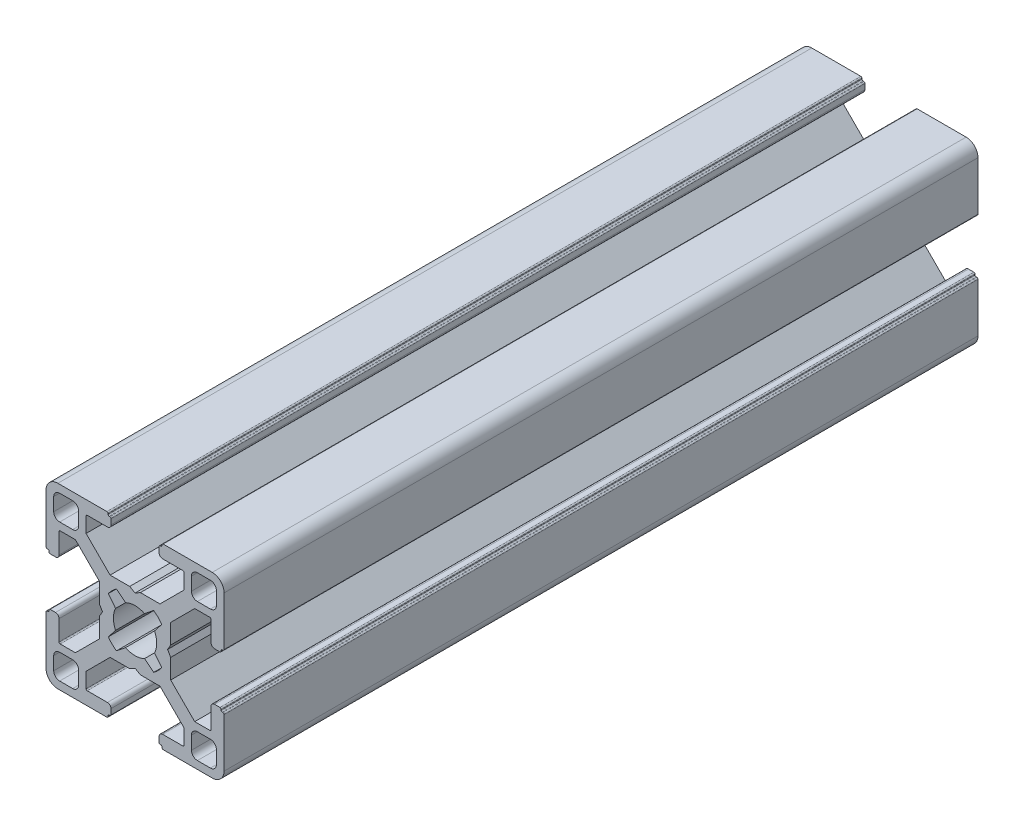
SolidWorks part; units mm, degrees
material "6061 Alloy"
ref_plane "Front" through (0, 0, 0) normal (0, 0, 1) x (1, 0, 0)
ref_plane "Top" through (0, 0, 0) normal (0, 1, 0) x (1, 0, 0)
ref_plane "Right" through (0, 0, 0) normal (1, 0, 0) x (0, 0, -1)
sketch "Sketch1" plane through (0, 0, 0) normal (0, 0, 1) x (1, 0, 0)
  line L0 (13.7, 12.7) -> (13.7, 10.5)
  line L1 (10.5, 9.5) -> (12.7, 9.5)
  line L2 (9.5, 12.7) -> (9.5, 10.5)
  line L3 (10.5, 13.7) -> (12.7, 13.7)
  line L4 (3.1359, 4.5184) -> (1.6001, 3.2806)
  line L5 (3.2806, 1.6001) -> (4.5053, 3.1547)
  line L6 (6.0045, 0.9) -> (5.4849, 0)
  line L7 (6.0045, 4.2045) -> (6.0045, 0.9)
  line L8 (0, -5.4849) -> (0.9, -6)
  line L9 (0.9, -6) -> (4.2045, -6)
  line L10 (4.2045, -6) -> (8.25, -10.05)
  line L11 (8.25, -10.05) -> (8.25, -12.6)
  line L12 (4.65, -12.8) -> (8.05, -12.8)
  line L13 (4.05, -14.3) -> (4.05, -13.4)
  line L14 (4.25, -14.5) -> (4.35, -14.5)
  line L15 (4.55, -14.8) -> (4.55, -14.7)
  line L16 (4.75, -15) -> (13, -15)
  line L17 (15, -13) -> (15, -4.75)
  line L18 (14.7, -4.55) -> (14.8, -4.55)
  line L19 (14.5, -4.35) -> (14.5, -4.25)
  line L20 (13.4, -4.05) -> (14.3, -4.05)
  line L21 (12.8, -8.05) -> (12.8, -4.65)
  line L22 (12.6, -8.25) -> (10.05, -8.25)
  line L23 (10.05, -8.25) -> (6.0045, -4.2045)
  line L24 (6.0045, -4.2045) -> (6.0045, -0.9)
  line L25 (6.0045, -0.9) -> (5.4849, 0)
  line L26 (10.05, 8.25) -> (6.0045, 4.2045)
  line L27 (12.6, 8.25) -> (10.05, 8.25)
  line L28 (12.8, 8.05) -> (12.8, 4.65)
  line L29 (13.4, 4.05) -> (14.3, 4.05)
  line L30 (14.5, 4.35) -> (14.5, 4.25)
  line L31 (14.7, 4.55) -> (14.8, 4.55)
  line L32 (15, 13) -> (15, 4.75)
  line L33 (4.75, 15) -> (13, 15)
  line L34 (4.55, 14.8) -> (4.55, 14.7)
  line L35 (4.25, 14.5) -> (4.35, 14.5)
  line L36 (4.05, 14.3) -> (4.05, 13.4)
  line L37 (4.65, 12.8) -> (8.05, 12.8)
  line L38 (8.25, 10.05) -> (8.25, 12.6)
  line L39 (4.2045, 6) -> (8.25, 10.05)
  line L40 (0.9, 6) -> (4.2045, 6)
  line L41 (0, 5.4849) -> (0.9, 6)
  line L42 (-13.7, -12.7) -> (-13.7, -10.5)
  line L43 (-10.5, -9.5) -> (-12.7, -9.5)
  line L44 (-9.5, -12.7) -> (-9.5, -10.5)
  line L45 (-10.5, -13.7) -> (-12.7, -13.7)
  line L46 (-3.1359, -4.5184) -> (-1.6001, -3.2806)
  line L47 (-3.2806, -1.6001) -> (-4.5053, -3.1547)
  line L48 (0, 5.4849) -> (-0.9, 6)
  line L49 (-0.9, 6) -> (-4.2045, 6)
  line L50 (-4.2045, 6) -> (-8.25, 10.05)
  line L51 (-8.25, 10.05) -> (-8.25, 12.6)
  line L52 (-4.65, 12.8) -> (-8.05, 12.8)
  line L53 (-4.05, 14.3) -> (-4.05, 13.4)
  line L54 (-4.25, 14.5) -> (-4.35, 14.5)
  line L55 (-4.55, 14.8) -> (-4.55, 14.7)
  line L56 (-4.75, 15) -> (-13, 15)
  line L57 (-15, 13) -> (-15, 4.75)
  line L58 (-14.7, 4.55) -> (-14.8, 4.55)
  line L59 (-14.5, 4.35) -> (-14.5, 4.25)
  line L60 (-13.4, 4.05) -> (-14.3, 4.05)
  line L61 (-12.8, 8.05) -> (-12.8, 4.65)
  line L62 (-12.6, 8.25) -> (-10.05, 8.25)
  line L63 (-10.05, 8.25) -> (-6.0045, 4.2045)
  line L64 (-6.0045, -0.9) -> (-5.4849, 0)
  line L65 (-6.0045, -4.2045) -> (-6.0045, -0.9)
  line L66 (-10.05, -8.25) -> (-6.0045, -4.2045)
  line L67 (-12.6, -8.25) -> (-10.05, -8.25)
  line L68 (-12.8, -8.05) -> (-12.8, -4.65)
  line L69 (-13.4, -4.05) -> (-14.3, -4.05)
  line L70 (-14.5, -4.35) -> (-14.5, -4.25)
  line L71 (-14.7, -4.55) -> (-14.8, -4.55)
  line L72 (-15, -13) -> (-15, -4.75)
  line L73 (-4.75, -15) -> (-13, -15)
  line L74 (-4.55, -14.8) -> (-4.55, -14.7)
  line L75 (-4.25, -14.5) -> (-4.35, -14.5)
  line L76 (-4.05, -14.3) -> (-4.05, -13.4)
  line L77 (3.2806, -1.6001) -> (4.5053, -3.1547)
  line L78 (3.1359, -4.5184) -> (1.6001, -3.2806)
  line L79 (-4.65, -12.8) -> (-8.05, -12.8)
  line L80 (-8.25, -10.05) -> (-8.25, -12.6)
  line L81 (-4.2045, -6) -> (-8.25, -10.05)
  line L82 (-0.9, -6) -> (-4.2045, -6)
  line L83 (0, -5.4849) -> (-0.9, -6)
  line L84 (10.5, -13.7) -> (12.7, -13.7)
  line L85 (9.5, -12.7) -> (9.5, -10.5)
  line L86 (10.5, -9.5) -> (12.7, -9.5)
  line L87 (13.7, -12.7) -> (13.7, -10.5)
  line L88 (-6.0045, 4.2045) -> (-6.0045, 0.9)
  line L89 (-6.0045, 0.9) -> (-5.4849, 0)
  line L90 (-3.2806, 1.6001) -> (-4.5053, 3.1547)
  line L91 (-3.1359, 4.5184) -> (-1.6001, 3.2806)
  line L92 (-10.5, 13.7) -> (-12.7, 13.7)
  line L93 (-9.5, 12.7) -> (-9.5, 10.5)
  line L94 (-10.5, 9.5) -> (-12.7, 9.5)
  line L95 (-13.7, 12.7) -> (-13.7, 10.5)
  line L96 (-23.4857, 0) -> (20.9308, 0) construction
  line L97 (0, 17.9563) -> (0, -17.361) construction
  arc A0 (13.7, 12.7) -> (12.7, 13.7) centre (12.7, 12.7) ccw
  arc A1 (12.7, 9.5) -> (13.7, 10.5) centre (12.7, 10.5) ccw
  arc A2 (9.5, 10.5) -> (10.5, 9.5) centre (10.5, 10.5) ccw
  arc A3 (10.5, 13.7) -> (9.5, 12.7) centre (10.5, 12.7) ccw
  arc A4 (1.6001, 3.2806) -> (-1.6001, 3.2806) centre (0, 0) ccw
  arc A5 (8.25, -12.6) -> (8.05, -12.8) centre (8.05, -12.6) cw
  arc A6 (4.65, -12.8) -> (4.05, -13.4) centre (4.65, -13.4) ccw
  arc A7 (4.05, -14.3) -> (4.25, -14.5) centre (4.25, -14.3) ccw
  arc A8 (4.35, -14.5) -> (4.55, -14.7) centre (4.35, -14.7) cw
  arc A9 (4.55, -14.8) -> (4.75, -15) centre (4.75, -14.8) ccw
  arc A10 (13, -15) -> (15, -13) centre (13, -13) ccw
  arc A11 (15, -4.75) -> (14.8, -4.55) centre (14.8, -4.75) ccw
  arc A12 (14.7, -4.55) -> (14.5, -4.35) centre (14.7, -4.35) cw
  arc A13 (14.5, -4.25) -> (14.3, -4.05) centre (14.3, -4.25) ccw
  arc A14 (13.4, -4.05) -> (12.8, -4.65) centre (13.4, -4.65) ccw
  arc A15 (12.8, -8.05) -> (12.6, -8.25) centre (12.6, -8.05) cw
  arc A16 (4.5053, 3.1547) -> (3.1359, 4.5184) centre (0, 0) ccw
  arc A17 (12.8, 8.05) -> (12.6, 8.25) centre (12.6, 8.05) ccw
  arc A18 (13.4, 4.05) -> (12.8, 4.65) centre (13.4, 4.65) cw
  arc A19 (14.5, 4.25) -> (14.3, 4.05) centre (14.3, 4.25) cw
  arc A20 (14.7, 4.55) -> (14.5, 4.35) centre (14.7, 4.35) ccw
  arc A21 (15, 4.75) -> (14.8, 4.55) centre (14.8, 4.75) cw
  arc A22 (13, 15) -> (15, 13) centre (13, 13) cw
  arc A23 (4.55, 14.8) -> (4.75, 15) centre (4.75, 14.8) cw
  arc A24 (4.35, 14.5) -> (4.55, 14.7) centre (4.35, 14.7) ccw
  arc A25 (4.05, 14.3) -> (4.25, 14.5) centre (4.25, 14.3) cw
  arc A26 (4.65, 12.8) -> (4.05, 13.4) centre (4.65, 13.4) cw
  arc A27 (8.25, 12.6) -> (8.05, 12.8) centre (8.05, 12.6) ccw
  arc A28 (-13.7, -12.7) -> (-12.7, -13.7) centre (-12.7, -12.7) ccw
  arc A29 (-12.7, -9.5) -> (-13.7, -10.5) centre (-12.7, -10.5) ccw
  arc A30 (-9.5, -10.5) -> (-10.5, -9.5) centre (-10.5, -10.5) ccw
  arc A31 (-10.5, -13.7) -> (-9.5, -12.7) centre (-10.5, -12.7) ccw
  arc A32 (-4.5053, -3.1547) -> (-3.1359, -4.5184) centre (0, 0) ccw
  arc A33 (-3.2806, 1.6001) -> (-3.2806, -1.6001) centre (0, 0) ccw
  arc A34 (-8.25, 12.6) -> (-8.05, 12.8) centre (-8.05, 12.6) cw
  arc A35 (-4.65, 12.8) -> (-4.05, 13.4) centre (-4.65, 13.4) ccw
  arc A36 (-4.05, 14.3) -> (-4.25, 14.5) centre (-4.25, 14.3) ccw
  arc A37 (-4.35, 14.5) -> (-4.55, 14.7) centre (-4.35, 14.7) cw
  arc A38 (-4.55, 14.8) -> (-4.75, 15) centre (-4.75, 14.8) ccw
  arc A39 (-13, 15) -> (-15, 13) centre (-13, 13) ccw
  arc A40 (-15, 4.75) -> (-14.8, 4.55) centre (-14.8, 4.75) ccw
  arc A41 (-14.7, 4.55) -> (-14.5, 4.35) centre (-14.7, 4.35) cw
  arc A42 (-14.5, 4.25) -> (-14.3, 4.05) centre (-14.3, 4.25) ccw
  arc A43 (-13.4, 4.05) -> (-12.8, 4.65) centre (-13.4, 4.65) ccw
  arc A44 (-12.8, 8.05) -> (-12.6, 8.25) centre (-12.6, 8.05) cw
  arc A45 (-4.5053, 3.1547) -> (-3.1359, 4.5184) centre (0, 0) cw
  arc A46 (-12.8, -8.05) -> (-12.6, -8.25) centre (-12.6, -8.05) ccw
  arc A47 (-13.4, -4.05) -> (-12.8, -4.65) centre (-13.4, -4.65) cw
  arc A48 (-14.5, -4.25) -> (-14.3, -4.05) centre (-14.3, -4.25) cw
  arc A49 (3.2806, 1.6001) -> (3.2806, -1.6001) centre (0, 0) cw
  arc A50 (4.5053, -3.1547) -> (3.1359, -4.5184) centre (0, 0) cw
  arc A51 (1.6001, -3.2806) -> (-1.6001, -3.2806) centre (0, 0) cw
  arc A52 (-14.7, -4.55) -> (-14.5, -4.35) centre (-14.7, -4.35) ccw
  arc A53 (-15, -4.75) -> (-14.8, -4.55) centre (-14.8, -4.75) cw
  arc A54 (-13, -15) -> (-15, -13) centre (-13, -13) cw
  arc A55 (-4.55, -14.8) -> (-4.75, -15) centre (-4.75, -14.8) cw
  arc A56 (10.5, -13.7) -> (9.5, -12.7) centre (10.5, -12.7) cw
  arc A57 (9.5, -10.5) -> (10.5, -9.5) centre (10.5, -10.5) cw
  arc A58 (12.7, -9.5) -> (13.7, -10.5) centre (12.7, -10.5) cw
  arc A59 (13.7, -12.7) -> (12.7, -13.7) centre (12.7, -12.7) cw
  arc A60 (-4.35, -14.5) -> (-4.55, -14.7) centre (-4.35, -14.7) ccw
  arc A61 (-4.05, -14.3) -> (-4.25, -14.5) centre (-4.25, -14.3) cw
  arc A62 (-4.65, -12.8) -> (-4.05, -13.4) centre (-4.65, -13.4) cw
  arc A63 (-8.25, -12.6) -> (-8.05, -12.8) centre (-8.05, -12.6) ccw
  arc A64 (-10.5, 13.7) -> (-9.5, 12.7) centre (-10.5, 12.7) cw
  arc A65 (-9.5, 10.5) -> (-10.5, 9.5) centre (-10.5, 10.5) cw
  arc A66 (-12.7, 9.5) -> (-13.7, 10.5) centre (-12.7, 10.5) cw
  arc A67 (-13.7, 12.7) -> (-12.7, 13.7) centre (-12.7, 12.7) cw
  point P81 (15, 15)
  point P82 (0, 15)
  point P203 (0, -15)
  point P204 (15, -15)
  point P206 (0, 0)
  point P207 (15, 0)
  point P219 (-15, 0)
  point P220 (-15, -15)
  point P221 (-15, 15)
  dimension "D6" = 7.3
  dimension "D7" = 11
  dimension "D1" = 30
  dimension "D2" = 15
  dimension "D3" = 30
  dimension "D4" = 8.1
  dimension "D5" = 9
  dimension "D8" = 8.1
extrude "Boss-Extrude1" add sketch "Sketch1" along normal blind 127
